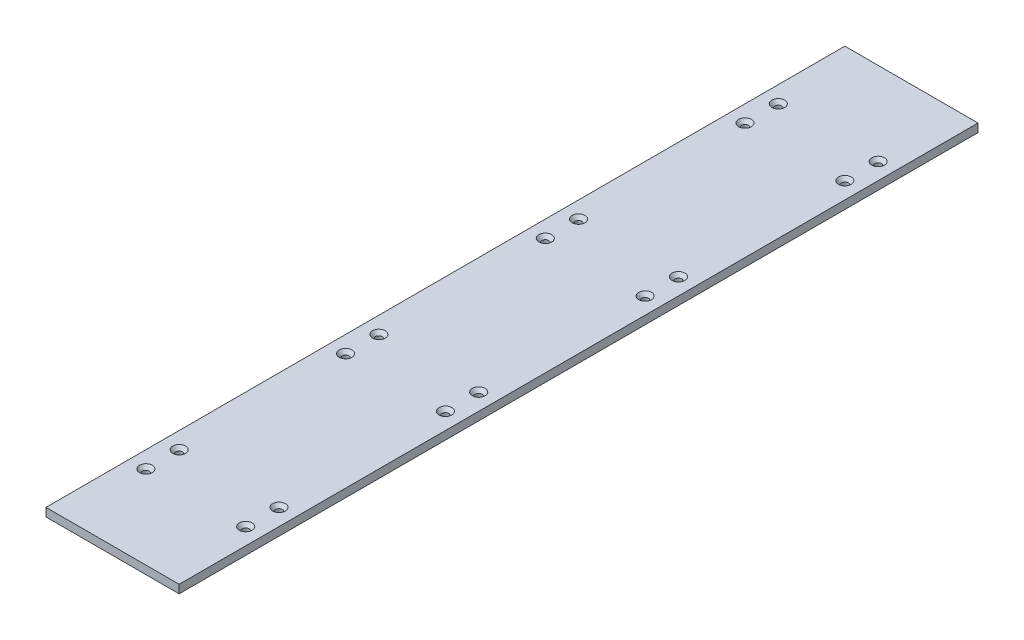
SolidWorks part; units mm, degrees
ref_plane "Front Plane" through (0, 0, 0) normal (0, 0, 1) x (1, 0, 0)
ref_plane "Top Plane" through (0, 0, 0) normal (0, 1, 0) x (1, 0, 0)
ref_plane "Right Plane" through (0, 0, 0) normal (1, 0, 0) x (0, 0, -1)
sketch "Sketch1" plane through (0, 0, 0) normal (0, 1, 0) x (1, 0, 0)
  line L1 (-50.8, -304.8) -> (50.8, -304.8)
  line L2 (-50.8, -304.8) -> (-50.8, 304.8)
  line L3 (-50.8, 304.8) -> (50.8, 304.8)
  line L4 (50.8, -304.8) -> (50.8, 304.8)
  line L5 (-50.8, -304.8) -> (50.8, 304.8) construction
  line L6 (-50.8, 304.8) -> (50.8, -304.8) construction
  point P0 (0, 0)
  dimension "D1" = 101.6
  dimension "D2" = 609.6
extrude "Boss-Extrude1" add sketch "Sketch1" along normal mid plane 6.35
sketch "Sketch2" plane through (0, 3.175, 0) normal (0, 1, 0) x (1, 0, 0)
  line L0 (-38.1, -101.6) -> (-38.1, -127) construction
  line L1 (-34.925, -101.6) -> (-34.925, -127)
  line L2 (-41.275, -101.6) -> (-41.275, -127)
  line L3 (-38.1, -228.6) -> (-38.1, -254) construction
  line L4 (-34.925, -228.6) -> (-34.925, -254)
  line L5 (-41.275, -228.6) -> (-41.275, -254)
  line L6 (-50.8, 304.8) -> (-50.8, -304.8) construction
  line L7 (-50.8, -304.8) -> (50.8, -304.8) construction
  arc A0 (-34.925, -101.6) -> (-41.275, -101.6) centre (-38.1, -101.6) ccw
  arc A1 (-41.275, -127) -> (-34.925, -127) centre (-38.1, -127) ccw
  arc A2 (-34.925, -228.6) -> (-41.275, -228.6) centre (-38.1, -228.6) ccw
  arc A3 (-41.275, -254) -> (-34.925, -254) centre (-38.1, -254) ccw
  point P2 (-38.1, -114.3)
  point P7 (-38.1, -241.3)
  dimension "D4" = 63.5
  dimension "D1" = 6.35
  dimension "D2" = 25.4
  dimension "D3" = 12.7
  dimension "D5" = 127
extrude "Cut-Extrude1" [suppressed] cut sketch "Sketch2" against normal through all
mirror "Mirror1" [suppressed] about plane through (0, 0, 0) normal (0, 0, 1)
mirror "Mirror2" [suppressed] about plane through (0, 0, 0) normal (1, 0, 0)
sketch "Sketch3" plane through (0, 3.175, 0) normal (0, 1, 0) x (1, 0, 0)
  line L0 (-50.8, -304.8) -> (50.8, -304.8) construction
  line L1 (-50.8, 304.8) -> (-50.8, -304.8) construction
  point P0 (-38.1, -215.9)
  point P1 (-38.1, -241.3)
  point P2 (-38.1, -88.9)
  point P3 (-38.1, -63.5)
  dimension "D1" = 25.4
  dimension "D2" = 25.4
  dimension "D3" = 63.5
  dimension "D4" = 127
  dimension "D5" = 12.7
hole_wizard "CSK for #10 Flat Head Machine Screw1" positions "Sketch4" profile "Sketch6" countersink size "#10" standard "ANSI Inch" end condition through all
sketch "Sketch4" plane through (0, 3.175, 0) normal (0, 1, 0) x (1, 0, 0)
  point P0 (-38.1, -88.9)
  point P3 (-38.1, -63.5)
  point P6 (-38.1, -215.9)
  point P9 (-38.1, -241.3)
sketch "Sketch6" plane through (-38.1, 3.175, 88.9) normal (1, 0, 0) x (0, 0, 1)
  line L0 (0, 0) -> (0, 6.35)
  line L1 (0, 6.35) -> (2.5527, 6.35)
  line L2 (2.5527, 6.35) -> (2.5527, 2.6882)
  line L3 (2.5527, 2.6882) -> (4.8895, 0)
  line L5 (4.8895, 0) -> (0, 0)
  line L6 (-2.5527, 2.6882) -> (-4.8895, 0) construction
  line L11 (0, -6.35) -> (0, 107.95) construction
  dimension "Thru Hole Dia." = 5.1054
  dimension "Thru Hole Depth" = 6.35
  dimension "Near C'Sink Dia." = 9.779
  dimension "Near C'Sink Angle" = 82
mirror "Mirror3" about plane through (0, 0, 0) normal (0, 0, 1) of "CSK for #10 Flat Head Machine Screw1"
mirror "Mirror4" about plane through (0, 0, 0) normal (1, 0, 0) of "Mirror3", "CSK for #10 Flat Head Machine Screw1"
